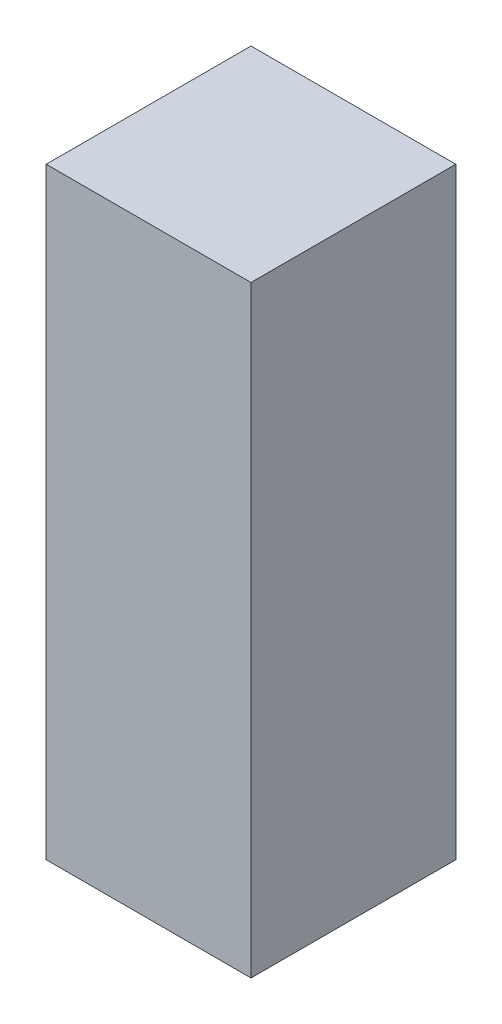
SolidWorks part; units mm, degrees
ref_plane "前视基准面" through (0, 0, 0) normal (0, 0, 1) x (1, 0, 0)
ref_plane "上视基准面" through (0, 0, 0) normal (0, 1, 0) x (1, 0, 0)
ref_plane "右视基准面" through (0, 0, 0) normal (1, 0, 0) x (0, 0, -1)
other "Configuration Table"
sketch "草图1" plane through (0, 0, 0) normal (0, 1, 0) x (1, 0, 0)
  line L1 (-0.85, 0.85) -> (0.85, 0.85)
  line L2 (-0.85, 0.85) -> (-0.85, -0.85)
  line L3 (-0.85, -0.85) -> (0.85, -0.85)
  line L4 (0.85, 0.85) -> (0.85, -0.85)
  line L5 (-0.85, 0.85) -> (0.85, -0.85) construction
  line L6 (-0.85, -0.85) -> (0.85, 0.85) construction
  line L7 (-0.6, 0.6) -> (0.6, 0.6)
  line L8 (-0.6, 0.6) -> (-0.6, -0.6)
  line L9 (-0.6, -0.6) -> (0.6, -0.6)
  line L10 (0.6, 0.6) -> (0.6, -0.6)
  line L11 (-0.6, 0.6) -> (0.6, -0.6) construction
  line L12 (-0.6, -0.6) -> (0.6, 0.6) construction
  point P0 (0, 0)
  point P6 (0, 0)
  dimension "D1" = 1.2
  dimension "D2" = 1.7
extrude "凸台-拉伸1" add sketch "草图1" along normal blind 3
sketch "草图2" plane through (0, 3, 0) normal (0, 1, 0) x (1, 0, 0)
  line L1 (-0.85, 0.85) -> (0.85, 0.85)
  line L2 (-0.85, 0.85) -> (-0.85, -0.85)
  line L3 (-0.85, -0.85) -> (0.85, -0.85)
  line L4 (0.85, 0.85) -> (0.85, -0.85)
  line L5 (-0.85, 0.85) -> (0.85, -0.85) construction
  line L6 (-0.85, -0.85) -> (0.85, 0.85) construction
  point P0 (0, 0)
extrude "凸台-拉伸2" add sketch "草图2" along normal blind 2
